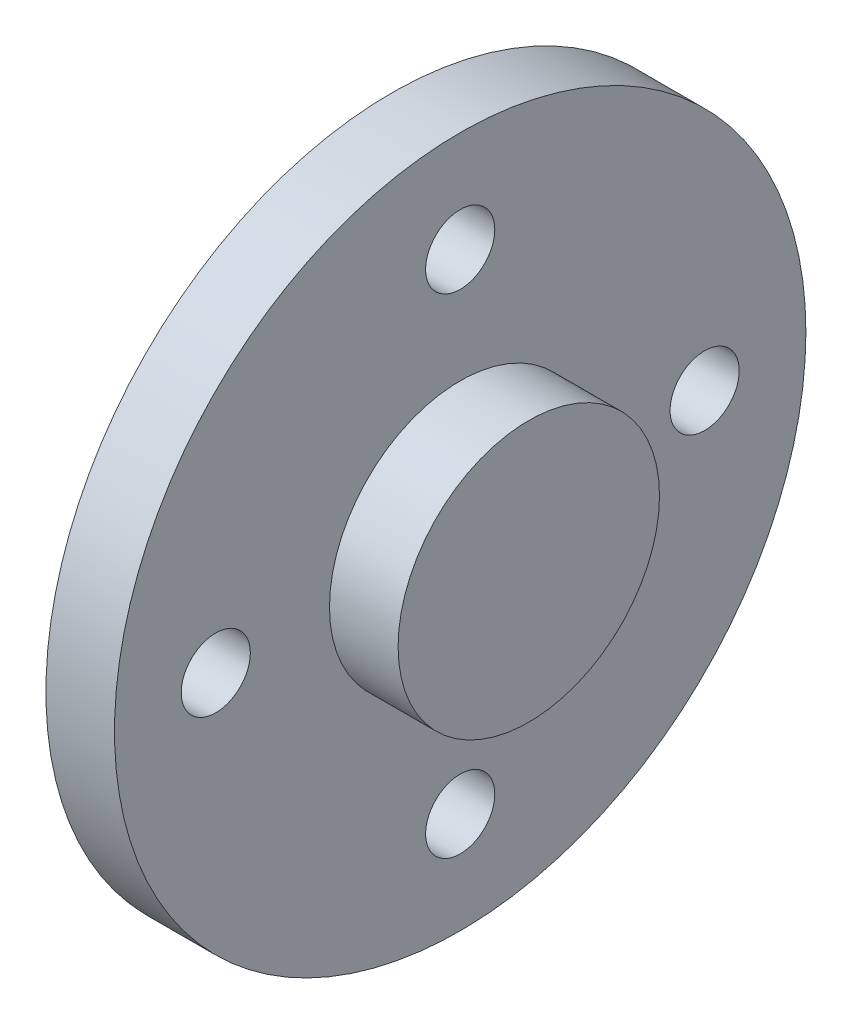
SolidWorks part; units mm, degrees
ref_plane "Front" through (0, 0, 0) normal (0, 0, 1) x (1, 0, 0)
ref_plane "Top" through (0, 0, 0) normal (0, 1, 0) x (1, 0, 0)
ref_plane "Right" through (0, 0, 0) normal (1, 0, 0) x (0, 0, -1)
sketch "Sketch1" plane through (0, 0, 0) normal (1, 0, 0) x (0, 0, -1)
  circle A0 centre (0, 0) radius 11.3137
  circle A1 centre (0, 11.3137) radius 1.6
  circle A2 centre (11.3137, 0) radius 1.6
  circle A3 centre (0, -11.3137) radius 1.6
  circle A4 centre (-11.3137, 0) radius 1.6
  circle A5 centre (0, 0) radius 16
extrude "Boss-Extrude1" add sketch "Sketch1" along normal blind 3.175 contours A5 A4 A0 A1 A2 A3 | A4 A0 A3 A2 A1
sketch "Sketch2" plane through (3.175, 0, 0) normal (1, 0, 0) x (0, 0, -1)
  circle A0 centre (0, 0) radius 6.05
extrude "Boss-Extrude2" add sketch "Sketch2" along normal blind 3.175
